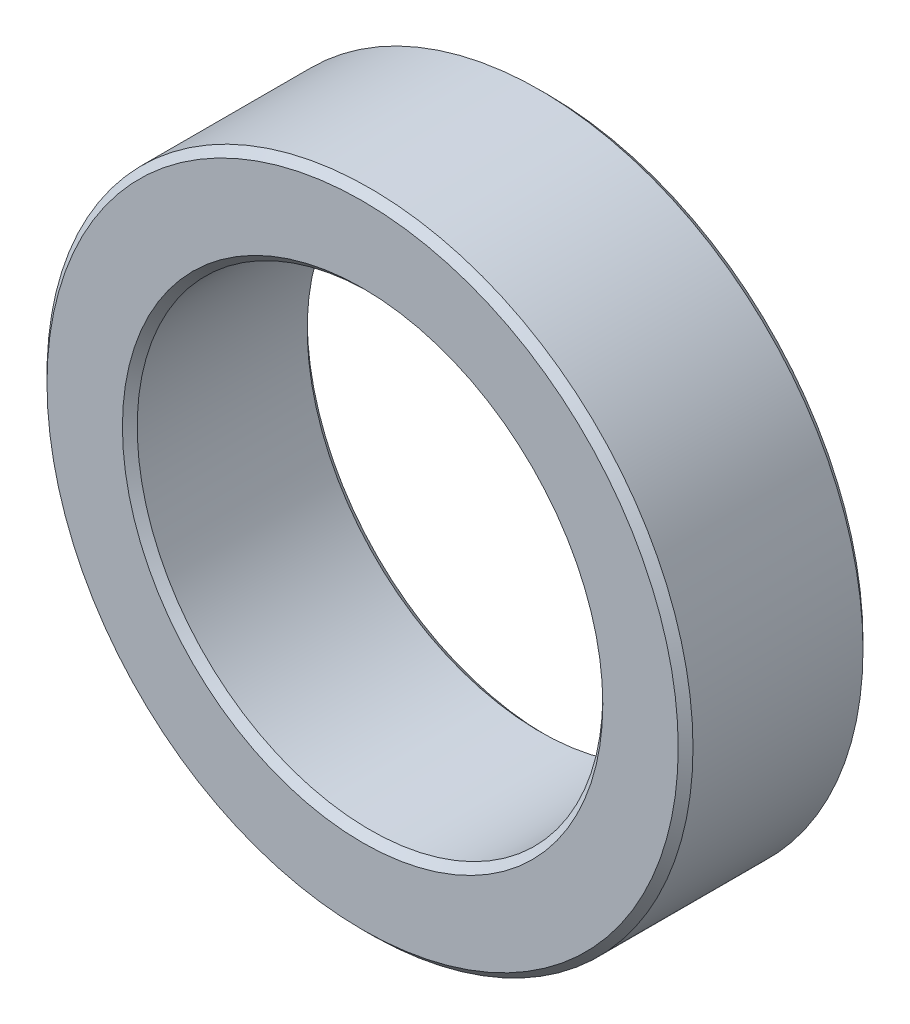
SolidWorks part; units mm, degrees
material "Hexcel AS4C (3000 Filaments)"
ref_plane "Front Plane" through (0, 0, 0) normal (0, 0, 1) x (1, 0, 0)
ref_plane "Top Plane" through (0, 0, 0) normal (0, 1, 0) x (1, 0, 0)
ref_plane "Right Plane" through (0, 0, 0) normal (1, 0, 0) x (0, 0, -1)
sketch "Sketch1" plane through (0, 0, 0) normal (0, 0, 1) x (1, 0, 0)
  circle A0 centre (0, 0) radius 5.5499
  circle A1 centre (0, 0) radius 4
  dimension "D1" = 8
  dimension "D2" = 11.0998
extrude "Boss-Extrude1" add sketch "Sketch1" along normal blind 3.175
chamfer "Chamfer1" distance 0.127 angle 45 4 edges at (4, 0, 0) (4, 0, 3.175) (5.5499, 0, 0) (5.5499, 0, 3.175)
equation "\"D1@Sketch1\"=8mm"
